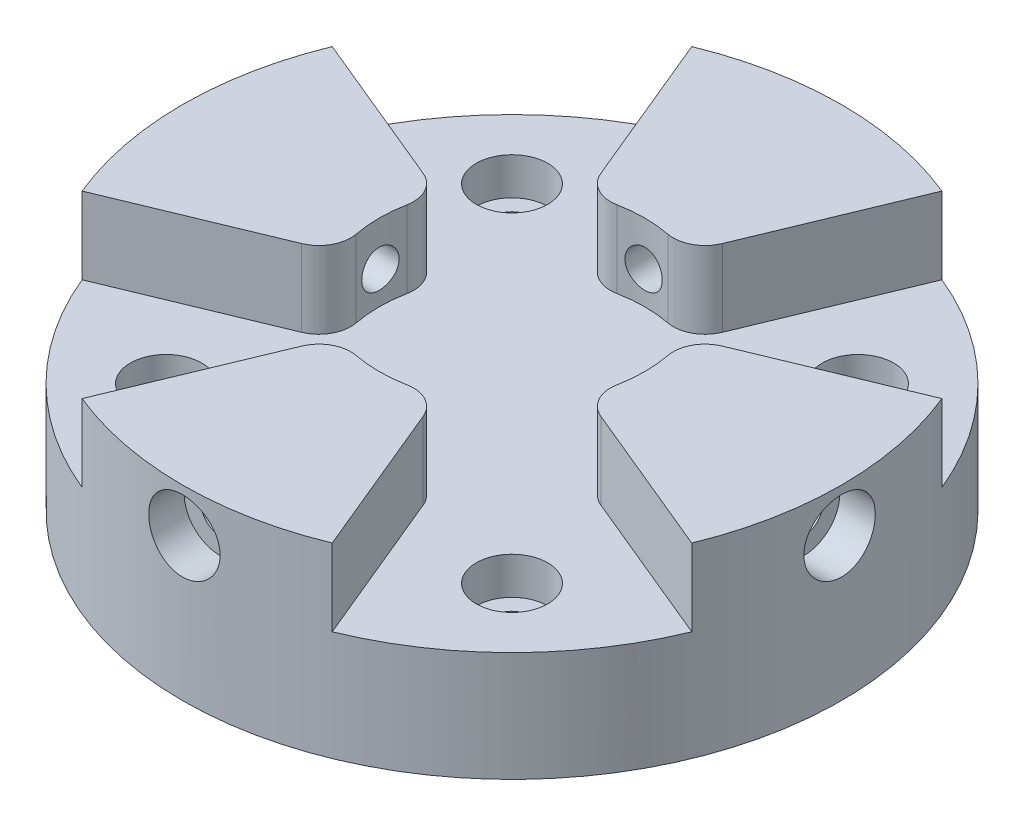
SolidWorks part; units mm, degrees
ref_plane "Front Plane" through (0, 0, 0) normal (0, 0, 1) x (1, 0, 0)
ref_plane "Top Plane" through (0, 0, 0) normal (0, 1, 0) x (1, 0, 0)
ref_plane "Right Plane" through (0, 0, 0) normal (1, 0, 0) x (0, 0, -1)
sketch "Sketch1" plane through (0, 0, 0) normal (0, 1, 0) x (1, 0, 0)
  circle A0 centre (0, 0) radius 30
  dimension "D1" = 60
extrude "Boss-Extrude1" add sketch "Sketch1" along normal blind 10
hole_wizard "CBORE for M3 Hex Socket Head Cap Screw1" positions "Sketch2" profile "Sketch3" counterbore size "M3" standard "ISO" end condition up to next
sketch "Sketch2" plane through (0, 10, 0) normal (0, 1, 0) x (1, 0, 0)
  line L1 (15.75, 15.75) -> (-15.75, 15.75)
  line L2 (-15.75, 15.75) -> (-15.75, -15.75)
  line L3 (-15.75, -15.75) -> (15.75, -15.75)
  line L4 (15.75, -15.75) -> (15.75, 15.75)
  circle A0 centre (0, 0) radius 22.2739 construction
  point P3 (15.75, 15.75)
  point P4 (-15.75, 15.75)
  point P5 (-15.75, -15.75)
  point P6 (15.75, -15.75)
  dimension "D1" = 31.5
sketch "Sketch3" plane through (15.75, 10, 15.75) normal (1, 0, 0) x (0, 0, 1)
  line L0 (0, 0) -> (0, 10)
  line L1 (0, 10) -> (1.7, 10)
  line L3 (1.7, 10) -> (1.7, 3.4)
  line L4 (1.7, 3.4) -> (3.25, 3.4)
  line L5 (3.25, 3.4) -> (3.25, 0)
  line L7 (3.25, 0) -> (0, 0)
  line L11 (0, -6.35) -> (0, 107.95) construction
  dimension "Thru Hole Dia." = 3.4
  dimension "Thru Hole Depth" = 10
  dimension "C'Bore Dia." = 6.5
  dimension "C'Bore Depth" = 3.4
sketch "Sketch5" plane through (0, 10, 0) normal (0, 1, 0) x (1, 0, 0)
  line L0 (0, 0) -> (-11.4805, -27.7164)
  line L1 (0, 0) -> (11.4805, -27.7164)
  circle A0 centre (0, 0) radius 30 construction
  circle A1 centre (0, 0) radius 30
  circle A2 centre (0, 0) radius 12
  circle M9 centre (0, 0) radius 30
  dimension "D1" = 18
  dimension "D2" = 45
extrude "Boss-Extrude2" add sketch "Sketch5" along normal blind 7 contours A2 L0 L1 M9
ref_plane "Plane1" through (0, 0, 30) normal (0, 0, 1) x (1, 0, 0)
hole_wizard "CBORE for M3 Hex Socket Head Cap Screw2" positions "Sketch6" profile "Sketch7" counterbore size "M3" standard "ISO" end condition up to next
sketch "Sketch6" plane through (0, 0, 30) normal (0, 0, 1) x (1, 0, 0)
  line L0 (11.4805, 17) -> (-11.4805, 17) construction
  point P0 (0, 13)
  dimension "D1" = 4
sketch "Sketch7" plane through (0, 13, 30) normal (1, 0, 0) x (0, -1, 0)
  line L0 (0, 0) -> (0, 18.9144)
  line L1 (0, 18.9144) -> (1.7, 18.9144)
  line L3 (1.7, 18.9144) -> (1.7, 3.4)
  line L4 (1.7, 3.4) -> (3.25, 3.4)
  line L5 (3.25, 3.4) -> (3.25, 0)
  line L7 (3.25, 0) -> (0, 0)
  line L11 (0, -6.35) -> (0, 107.95) construction
  dimension "Thru Hole Dia." = 3.4
  dimension "Thru Hole Depth" = 18.9144
  dimension "C'Bore Dia." = 6.5
  dimension "C'Bore Depth" = 3.4
pattern_circular "CirPattern1" count 4 over 360 about axis through (0, 0, 0) along (0, 1, 0) of "CBORE for M3 Hex Socket Head Cap Screw2", "Boss-Extrude2"
fillet "Fillet1" radius 3 8 edges at (-4.5922, 13.5, 11.0866) (4.5922, 13.5, 11.0866) (11.0866, 13.5, -4.5922) (-4.5922, 13.5, -11.0866) (11.0866, 13.5, 4.5922) (-11.0866, 13.5, 4.5922) (-11.0866, 13.5, -4.5922) (4.5922, 13.5, -11.0866)
sketch "Sketch8" plane through (0, 17, 0) normal (0, 1, 0) x (1, 0, 0)
  line L2 (-13.5782, -5.6243) -> (-27.7164, -11.4805) construction
  line L3 (-13.5782, 5.6243) -> (-27.7164, 11.4805) construction
  line L4 (-27.7547, -11.3881) -> (-13.6165, -5.5319)
  line L5 (-13.6165, 5.5319) -> (-27.7547, 11.3881)
  line L6 (-27.7547, -11.3881) -> (-13.6165, -5.5319)
  line L7 (-13.6165, 5.5319) -> (-27.7547, 11.3881)
  line L8 (-13.5782, -5.6243) -> (-27.7164, -11.4805)
  line L9 (-13.5782, 5.6243) -> (-27.7164, 11.4805)
  arc A0 (-27.7164, 11.4805) -> (-27.7164, -11.4805) centre (0, 0) ccw construction
  arc A1 (-27.7164, 11.4805) -> (-27.7164, -11.4805) centre (0, 0) ccw
  arc A5 (-13.5782, -5.6243) -> (-11.781, -2.2821) centre (-14.7263, -2.8526) ccw construction
  arc A6 (-11.781, 2.2821) -> (-13.5782, 5.6243) centre (-14.7263, 2.8526) ccw construction
  arc A7 (-11.781, 2.2821) -> (-11.781, -2.2821) centre (0, 0) ccw construction
  arc A8 (-13.6165, -5.5319) -> (-11.8792, -2.3011) centre (-14.7263, -2.8526) ccw
  arc A9 (-11.8792, 2.3011) -> (-11.8792, -2.3011) centre (0, 0) ccw
  arc A10 (-11.8792, 2.3011) -> (-13.6165, 5.5319) centre (-14.7263, 2.8526) ccw
  arc A11 (-13.6165, -5.5319) -> (-11.8792, -2.3011) centre (-14.7263, -2.8526) ccw
  arc A12 (-11.8792, 2.3011) -> (-11.8792, -2.3011) centre (0, 0) ccw
  arc A13 (-11.8792, 2.3011) -> (-13.6165, 5.5319) centre (-14.7263, 2.8526) ccw
  arc A14 (-13.5782, -5.6243) -> (-11.781, -2.2821) centre (-14.7263, -2.8526) ccw
  arc A15 (-11.781, 2.2821) -> (-13.5782, 5.6243) centre (-14.7263, 2.8526) ccw
  arc A16 (-11.781, 2.2821) -> (-11.781, -2.2821) centre (0, 0) ccw
  line M6 (-27.7164, -11.4805) -> (-13.5782, -5.6243)
  arc M7 (-13.5782, -5.6243) -> (-11.781, -2.2821) centre (-14.7263, -2.8526) ccw
  arc M8 (-11.781, -2.2821) -> (-11.781, 2.2821) centre (0, 0) cw
  arc M9 (-11.781, 2.2821) -> (-13.5782, 5.6243) centre (-14.7263, 2.8526) ccw
  line M10 (-13.5782, 5.6243) -> (-27.7164, 11.4805)
  arc M11 (-27.7164, 11.4805) -> (-27.7164, -11.4805) centre (0, 0) ccw
  dimension "D1" = 0.1
extrude "Cut-Extrude1" cut sketch "Sketch8" against normal up to surface (7 mm away) contours A13 A12 A11 L6 L7 M11 M6 M7 M8 M9 M10 up to face at (15.75, 10, -12.5)
pattern_circular "CirPattern2" count 4 over 360 about axis through (0, 0, 0) along (0, 1, 0) of "Cut-Extrude1"
